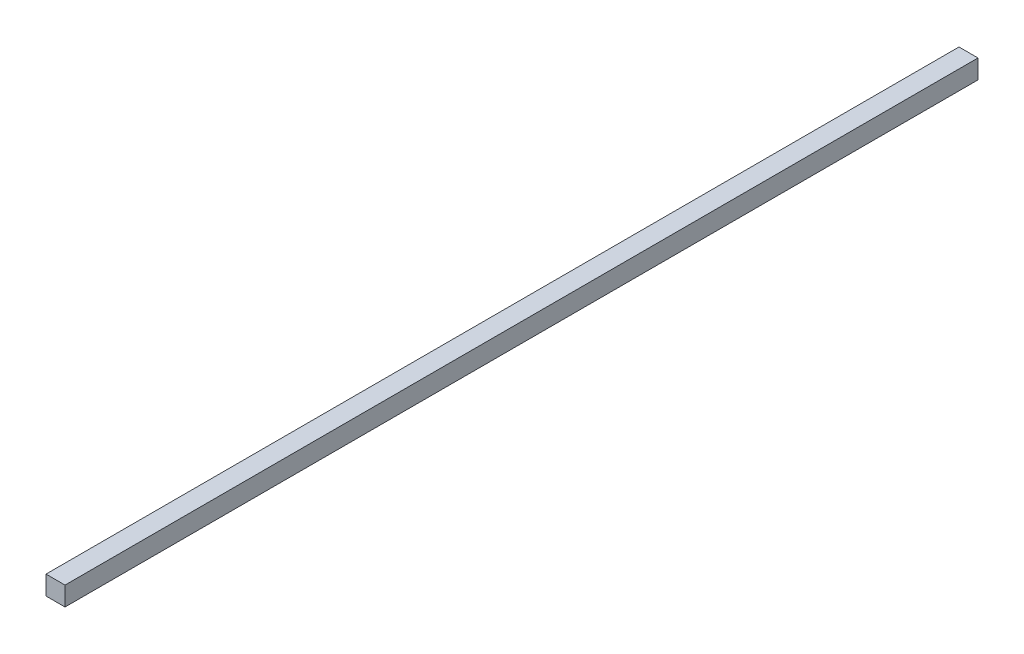
SolidWorks part; units mm, degrees
ref_plane "Front Plane" through (0, 0, 0) normal (0, 0, 1) x (1, 0, 0)
ref_plane "Top Plane" through (0, 0, 0) normal (0, 1, 0) x (1, 0, 0)
ref_plane "Right Plane" through (0, 0, 0) normal (1, 0, 0) x (0, 0, -1)
sketch "Sketch1" plane through (0, 0, 0) normal (0, 0, 1) x (1, 0, 0)
  line L1 (-11.3933, -2.1817) -> (-5.0433, -2.1817)
  line L2 (-11.3933, -2.1817) -> (-11.3933, 4.1683)
  line L3 (-11.3933, 4.1683) -> (-5.0433, 4.1683)
  line L4 (-5.0433, -2.1817) -> (-5.0433, 4.1683)
  dimension "D2" = 6.35
extrude "Boss-Extrude1" add sketch "Sketch1" along normal blind 304.8
equation "\"Bar width\" = 0.25in"
equation "\"Bar length\"= 12in"
equation "\"D2@Sketch1\"=\"Bar width\""
equation "\"D1@Boss-Extrude1\"=\"Bar length\""
equation "\"E Modulus\"= 850000"
equation "\"Cross Area\" = \"Bar width\" * \"Bar thickness\""
equation "\"Force\" = 250"
equation "\"deflection\"= ( ( \"Force\" * \"Bar length\" ) / ( \"Cross Area\" * \"E Modulus\" ) )"
equation "\"Bar thickness\" = 0.50in"
